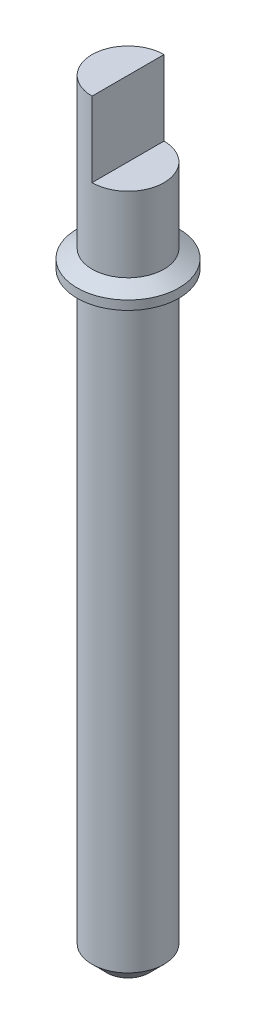
SolidWorks part; units mm, degrees
material "AISI 316 Stainless Steel Sheet (SS)"
ref_plane "Front Plane" through (0, 0, 0) normal (0, 0, 1) x (1, 0, 0)
ref_plane "Top Plane" through (0, 0, 0) normal (0, 1, 0) x (1, 0, 0)
ref_plane "Right Plane" through (0, 0, 0) normal (1, 0, 0) x (0, 0, -1)
sketch "Sketch1" plane through (0, 0, 0) normal (0, 0, 1) x (1, 0, 0)
  line L0 (0, 0) -> (0, 2.7193)
  line L1 (0, 2.7193) -> (0.6, 2.7193)
  line L2 (0.6, 2.7193) -> (0.6, 0.2193)
  line L3 (0.6, 0.2193) -> (0.85, 0.075)
  line L4 (0.85, 0.075) -> (0.85, -0.075)
  line L5 (0, 0) -> (0.85, 0) construction
  line L6 (0.6, -0.2193) -> (0.85, -0.075)
  line L7 (0.6, -0.2193) -> (0.6, -10.0693)
  line L8 (0, -10.0693) -> (0, 0)
  line L9 (0, -10.0693) -> (0.6, -10.0693)
  dimension "D1" = 0.6
  dimension "D2" = 120
  dimension "D3" = 0.075
  dimension "D4" = 2.5
  dimension "D5" = 0.25
  dimension "D6" = 9.85
revolve "Revolve1" add sketch "Sketch1" angle 360 about L0
sketch "Sketch2" plane through (0, 2.7193, 0) normal (0, 1, 0) x (1, 0, 0)
  line L0 (0, 0.6) -> (0, -0.6)
  arc A0 (0, 0.6) -> (0, -0.6) centre (0, 0) cw
  circle A1 centre (0, 0) radius 0.6 construction
  circle A2 centre (0, 0) radius 0.6 construction
extrude "Cut-Extrude1" cut sketch "Sketch2" against normal blind 1.25
chamfer "Chamfer1" distance 0.25 angle 45 1 edges at (0.6, -10.0693, 0)
